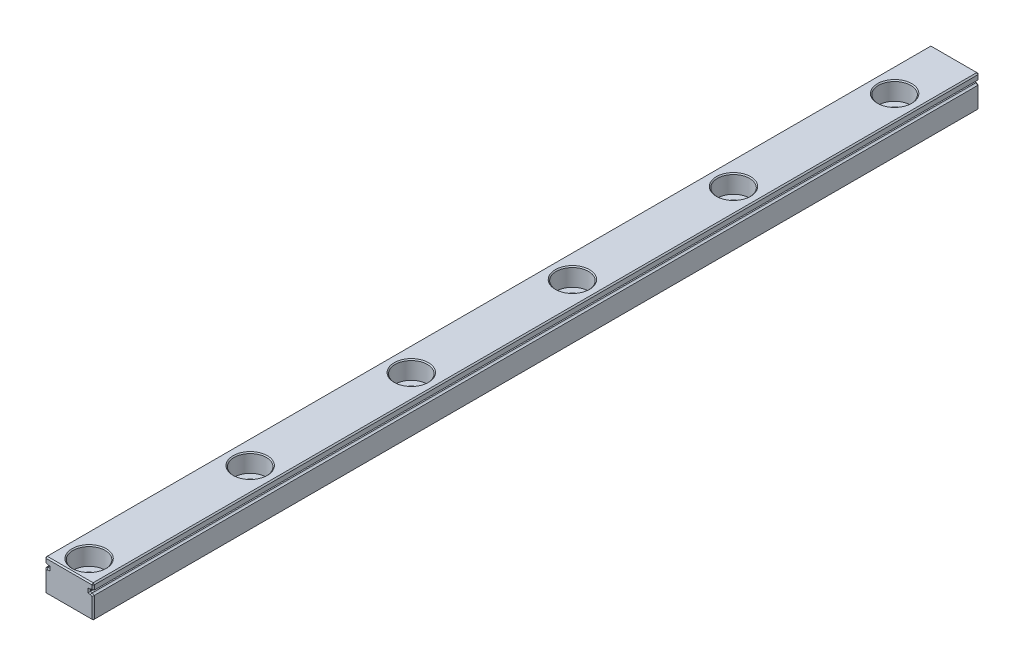
SolidWorks part; units mm, degrees
material "AISI 304"
ref_plane "Front Plane" through (0, 0, 0) normal (0, 0, 1) x (1, 0, 0)
ref_plane "Top Plane" through (0, 0, 0) normal (0, 1, 0) x (1, 0, 0)
ref_plane "Right Plane" through (0, 0, 0) normal (1, 0, 0) x (0, 0, -1)
sketch "Sketch1" plane through (0, 0, 0) normal (0, 0, 1) x (1, 0, 0)
  line L0 (0, 0) -> (0, 8) construction
  line L1 (0, 8) -> (12, 8)
  line L2 (0, 0) -> (12, 0)
  line L3 (0, 8) -> (0, 6.75)
  line L4 (0, 6.75) -> (0.5, 6.25) construction
  line L5 (0.5, 6.25) -> (1, 6.25)
  line L6 (0.5, 5.75) -> (0, 5.25) construction
  line L7 (0, 5.25) -> (0, 0)
  line L8 (1, 6.25) -> (1, 5.75)
  line L9 (1, 5.75) -> (0.5, 5.75)
  line L10 (0.5, 5.75) -> (0.75, 6) construction
  line L11 (0.75, 6) -> (0.5, 6.25) construction
  line L12 (0, 6.75) -> (0, 6.559)
  line L13 (0, 5.25) -> (0, 5.441)
  line L14 (6, 8) -> (6, 0) construction
  line L15 (11.25, 6) -> (11.5, 6.25) construction
  line L16 (11.5, 5.75) -> (11.25, 6) construction
  line L17 (11.5, 5.75) -> (12, 5.25) construction
  line L18 (12, 6.75) -> (11.5, 6.25) construction
  line L19 (12, 0) -> (12, 8) construction
  line L20 (12, 5.25) -> (12, 5.441)
  line L21 (12, 6.75) -> (12, 6.559)
  line L22 (11, 5.75) -> (11.5, 5.75)
  line L23 (11, 6.25) -> (11, 5.75)
  line L24 (12, 5.25) -> (12, 0)
  line L25 (11.5, 6.25) -> (11, 6.25)
  line L26 (12, 8) -> (12, 6.75)
  arc A0 (0, 5.441) -> (0.5, 5.75) centre (0, 6) ccw
  arc A1 (0.5, 6.25) -> (0, 6.559) centre (0, 6) ccw
  arc A2 (11.5, 6.25) -> (12, 6.559) centre (12, 6) cw
  arc A3 (12, 5.441) -> (11.5, 5.75) centre (12, 6) cw
  point P4 (1, 6)
  point P28 (11, 6)
  dimension "D1" = 8
  dimension "D2" = 6
  dimension "D3" = 0.5
  dimension "D4" = 45
  dimension "D5" = 2
  dimension "D6" = 1
extrude "Boss-Extrude1" add sketch "Sketch1" along normal blind 220
chamfer "Chamfer1" distance 0.3 angle 45 36 edges at (0, 0, 110) (12, 0, 110) (0, 8, 110) (12, 8, 110) (0.2939, 5.5245, 220) (0.75, 5.75, 220) (1, 6, 220) (0.75, 6.25, 220) (0.2939, 6.4755, 220) (0, 7.2795, 220) (6, 8, 220) (12, 7.2795, 220) (11.7061, 6.4755, 220) (11.25, 6.25, 220) (11, 6, 220) (11.25, 5.75, 220) (11.7061, 5.5245, 220) (12, 2.7205, 220) (6, 0, 220) (0, 2.7205, 220) (12, 2.7205, 0) (11.7061, 5.5245, 0) (11.25, 5.75, 0) (11, 6, 0) (11.25, 6.25, 0) (11.7061, 6.4755, 0) (12, 7.2795, 0) (6, 0, 0) (0, 2.7205, 0) (0.2939, 5.5245, 0) (0.75, 5.75, 0) (1, 6, 0) (0.75, 6.25, 0) (0.2939, 6.4755, 0) (0, 7.2795, 0) (6, 8, 0)
hole_wizard "CBORE for M5 Hex Head Bolt1" positions "3DSketch1" profile "Sketch3" counterbore size "M5" standard "ANSI Metric" end condition through all
sketch3d "3DSketch1"
  line L0 (6, 8, 0) -> (6, 8, 15) construction
  line L1 (11.7, 8, 0) -> (0.3, 8, 0) construction
  point P0 (6, 8, 15)
  dimension "D1" = 15
sketch "Sketch3" plane through (6, 8, 15) normal (1, 0, 0) x (0, 0, 1)
  line L0 (0, 0) -> (0, 8)
  line L1 (2.25, 7.75) -> (2.5, 8)
  line L2 (4, 4.5) -> (2.25, 4.5)
  line L3 (2.25, 4.5) -> (2.25, 7.75)
  line L5 (4, 4.5) -> (4, 0.25)
  line L6 (4, 0.25) -> (4.25, 0)
  line L7 (4.25, 0) -> (0, 0)
  line L8 (-4, 0.25) -> (-4.25, 0) construction
  line L11 (0, -6.35) -> (0, 107.95) construction
  line L12 (2.5, 8) -> (0, 8)
  line L13 (-2.25, 7.75) -> (-2.5, 8) construction
  dimension "Thru Hole Dia." = 4.5
  dimension "Thru Hole Depth" = 8
  dimension "C'Bore Dia." = 8
  dimension "C'Bore Depth" = 4.5
  dimension "Near C'Sink Dia." = 8.5
  dimension "Near C'Sink Angle" = 90
  dimension "Far C'Sink Dia." = 5
  dimension "Far C'Sink Angle" = 90
pattern_linear "LPattern1" count 6 spacing 40 along (0, 0, 1) of "CBORE for M5 Hex Head Bolt1"
